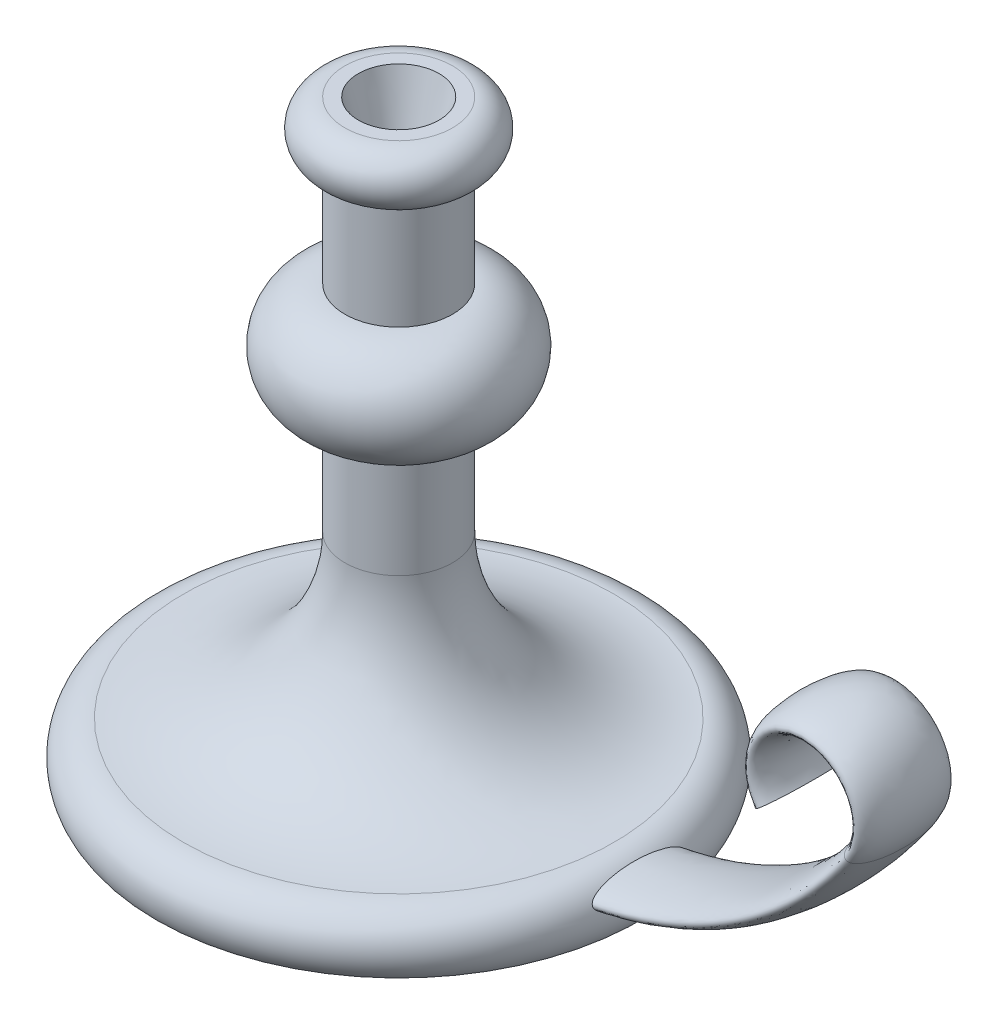
SolidWorks part; units mm, degrees
ref_plane "Front Plane" through (0, 0, 0) normal (0, 0, 1) x (1, 0, 0)
ref_plane "Top Plane" through (0, 0, 0) normal (0, 1, 0) x (1, 0, 0)
ref_plane "Right Plane" through (0, 0, 0) normal (1, 0, 0) x (0, 0, -1)
sketch "Sketch1" plane through (0, 0, 0) normal (0, 0, 1) x (1, 0, 0)
  line L0 (0, 0) -> (90, 0)
  line L1 (90, 0) -> (0, 0)
  line L2 (0, 0) -> (0, 220)
  line L3 (0, 220) -> (20, 220)
  line L4 (20, 200) -> (20, 160)
  line L5 (20, 120) -> (20, 80)
  arc A0 (20, 220) -> (20, 200) centre (20, 210) cw
  arc A1 (20, 160) -> (20, 120) centre (20, 140) cw
  arc A2 (20, 80) -> (80, 20) centre (80, 80) ccw
  arc A3 (80, 20) -> (90, 0) centre (80, 7.5) cw
  dimension "D5" = 20
  dimension "D7" = 60
  dimension "D4" = 10
  dimension "D8" = 12.5
  dimension "D1" = 220
  dimension "D2" = 90
  dimension "D3" = 20
  dimension "D6" = 40
  dimension "D9" = 80
revolve "Revolve2" add sketch "Sketch1" angle 360 about L2
sketch "Sketch2" plane through (0, 0, 0) normal (0, 0, 1) x (1, 0, 0)
  line L0 (0, 10) -> (60, 10)
  line L1 (0, 200) -> (0, 160) construction
  line L2 (-90, 0) -> (90, 0) construction
  arc A0 (60, 10) -> (183.5921, 75) centre (60, 160) ccw
  arc A1 (183.5921, 75) -> (150.6342, 75) centre (167.1131, 86.3333) ccw
  dimension "D2" = 150
  dimension "D4" = 20
  dimension "D1" = 60
  dimension "D3" = 65
  dimension "D5" = 10
sketch "Sketch3" plane through (0, 0, 0) normal (1, 0, 0) x (0, 0, -1)
  ellipse E0 centre (0, 10) end of major axis (17.5, 10) minor radius 5
  dimension "D1" = 10
  dimension "D2" = 35
sweep "Sweep1" add profiles "Sketch3" path "Sketch2"
sketch "Sketch4" plane through (0, 220, 0) normal (0, 1, 0) x (1, 0, 0)
  circle A0 centre (0, 0) radius 15
  dimension "D1" = 30
extrude "Cut-Extrude1" cut sketch "Sketch4" against normal blind 25 draft 15
